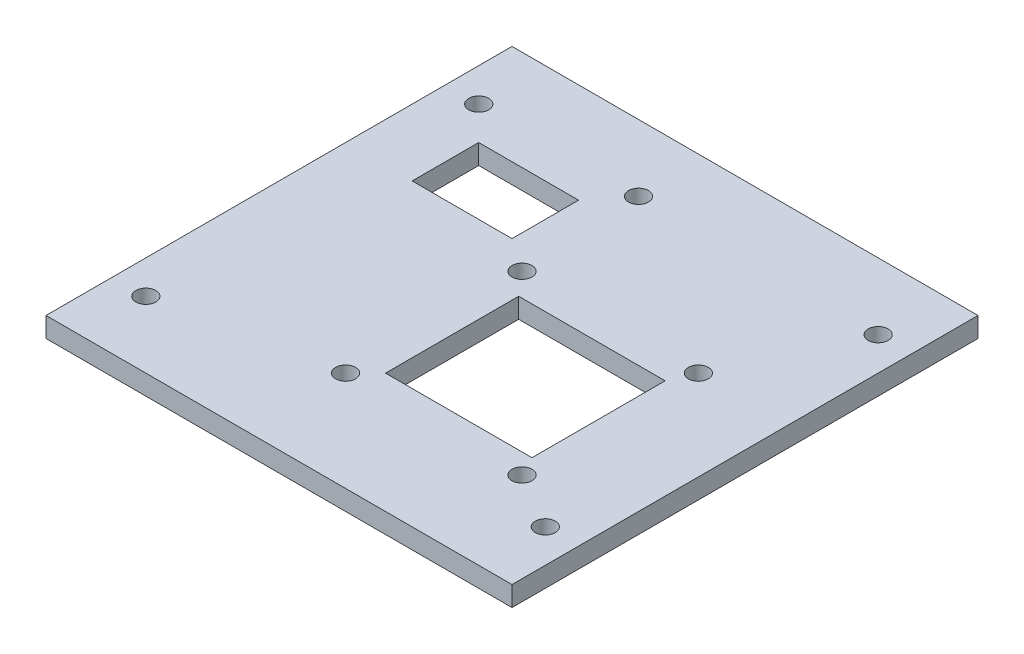
SolidWorks part; units mm, degrees
ref_plane "Front Plane" through (0, 0, 0) normal (0, 0, 1) x (1, 0, 0)
ref_plane "Top Plane" through (0, 0, 0) normal (0, 1, 0) x (1, 0, 0)
ref_plane "Right Plane" through (0, 0, 0) normal (1, 0, 0) x (0, 0, -1)
sketch "Sketch1" plane through (0, 0, 0) normal (0, 1, 0) x (1, 0, 0)
  line L1 (35, -35) -> (-35, -35)
  line L2 (35, -35) -> (35, 35)
  line L3 (35, 35) -> (-35, 35)
  line L4 (-35, -35) -> (-35, 35)
  line L5 (35, -35) -> (-35, 35) construction
  line L6 (35, 35) -> (-35, -35) construction
  point P0 (0, 0)
  dimension "D1" = 70
  dimension "D2" = 70
extrude "Boss-Extrude1" add sketch "Sketch1" along normal blind 3
sketch "Sketch2" plane through (0, 3, 0) normal (0, 1, 0) x (1, 0, 0)
  line L0 (-35, 35) -> (-35, -35) construction
  line L2 (35, 35) -> (-35, 35) construction
  line L3 (0, 0) -> (0, 35) construction
  line L4 (0, 0) -> (-35, 0) construction
  circle A0 centre (-30, 25) radius 1.5
  circle A1 centre (30, 25) radius 1.5
  circle A2 centre (30, -25) radius 1.5
  circle A3 centre (-30, -25) radius 1.5
  point P16 (0, 0)
  dimension "D1" = 3
  dimension "D2" = 5
  dimension "D3" = 10
extrude "Cut-Extrude1" cut sketch "Sketch2" against normal blind 3
sketch "Sketch3" plane through (0, 3, 0) normal (0, 1, 0) x (1, 0, 0)
  line L0 (35, -35) -> (35, 35) construction
  line L1 (35, 35) -> (-35, 35) construction
  line L2 (-35, -35) -> (35, -35) construction
  line L3 (-25, 20) -> (-10, 20)
  line L4 (-35, 35) -> (-35, -35) construction
  line L5 (-25, 20) -> (-25, 10)
  line L6 (20, -17) -> (-2, -17)
  line L7 (20, -17) -> (20, 3)
  line L8 (20, 3) -> (-2, 3)
  line L9 (-2, -17) -> (-2, 3)
  line L10 (20, -17) -> (-2, 3) construction
  line L11 (20, 3) -> (-2, -17) construction
  line L12 (-25, 10) -> (-10, 10)
  line L13 (-10, 20) -> (-10, 10)
  line L14 (-25, 20) -> (-10, 10) construction
  line L15 (-25, 10) -> (-10, 20) construction
  circle A0 centre (21.5, 6.5) radius 1.5
  circle A1 centre (21.5, -20) radius 1.5
  circle A2 centre (-5, -20) radius 1.5
  circle A3 centre (-6, 25) radius 1.5
  circle A5 centre (-5, 6.5) radius 1.5
  circle A6 centre (-30, 25) radius 1.5 construction
  point P0 (0, 0)
  point P3 (-17.5, 15)
  dimension "D1" = 3
  dimension "D2" = 15
  dimension "D3" = 5
  dimension "D6" = 26.5
  dimension "D7" = 15
  dimension "D10" = 10
  dimension "D11" = 3
  dimension "D12" = 24
  dimension "D13" = 10
  dimension "D4" = 20
  dimension "D5" = 22
  dimension "D8" = 10
  dimension "D9" = 15
  dimension "20" = 15
  dimension "D14" = 15
  dimension "D15" = 26.5
  dimension "D16" = 18
  dimension "26.5" = 26.5
extrude "Cut-Extrude2" cut sketch "Sketch3" against normal blind 3
